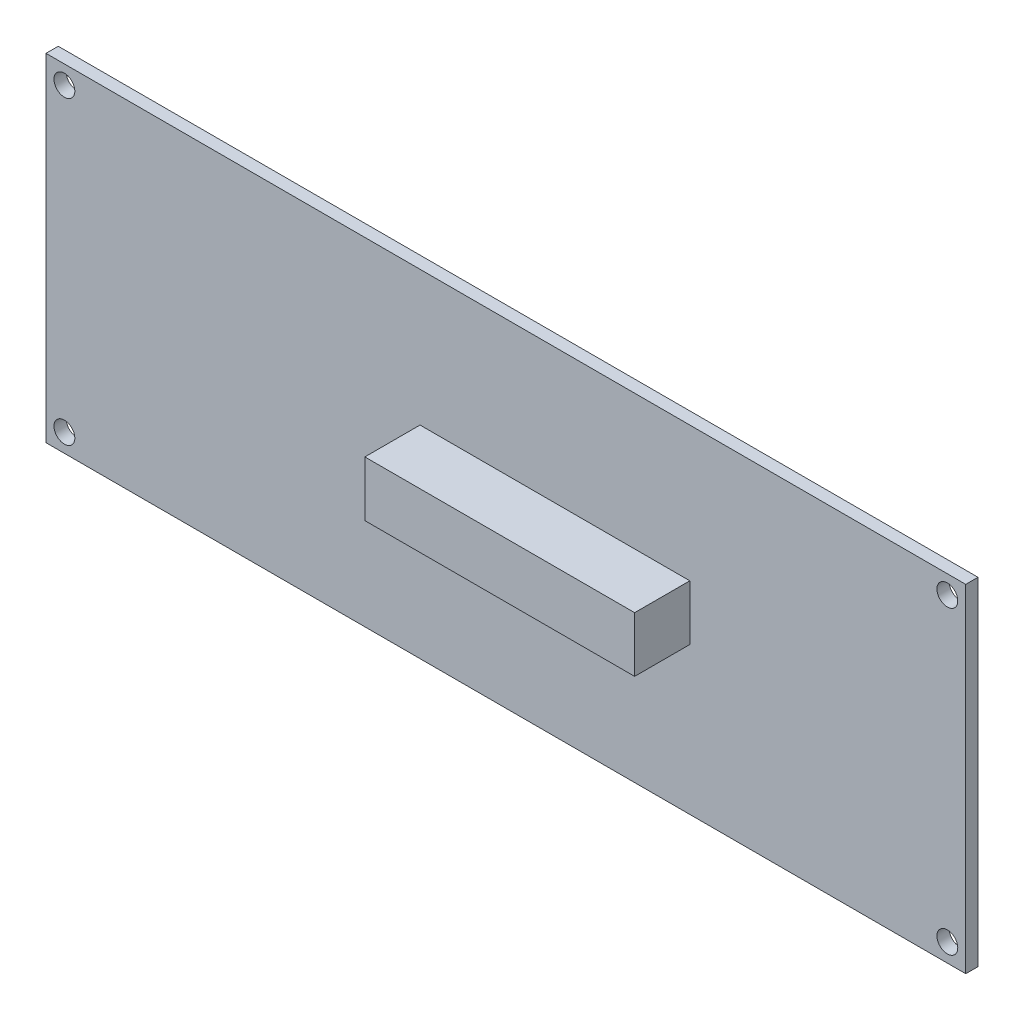
SolidWorks part; units mm, degrees
ref_plane "前基準面" through (0, 0, 0) normal (0, 0, 1) x (1, 0, 0)
ref_plane "上基準面" through (0, 0, 0) normal (0, 1, 0) x (1, 0, 0)
ref_plane "右基準面" through (0, 0, 0) normal (1, 0, 0) x (0, 0, -1)
sketch "草圖1" plane through (0, 0, 0) normal (0, 0, 1) x (1, 0, 0)
  line L0 (0, 27.5) -> (0, -27.5) construction
  line L1 (-75, 27.5) -> (75, 27.5)
  line L2 (-75, 27.5) -> (-75, -27.5)
  line L3 (-75, -27.5) -> (75, -27.5)
  line L4 (75, 27.5) -> (75, -27.5)
  line L6 (-75, 0) -> (75, 0) construction
  circle A0 centre (-72, 24.5) radius 1.7
  circle A1 centre (72, 24.5) radius 1.7
  circle A2 centre (72, -24.5) radius 1.7
  circle A3 centre (-72, -24.5) radius 1.7
  point P4 (0, 27.5)
  point P6 (-75, 0)
  dimension "D5" = 3.4
  dimension "D1" = 150
  dimension "D2" = 55
  dimension "D3" = 3
  dimension "D4" = 3
extrude "填料-伸長1" add sketch "草圖1" along normal blind 2
sketch "草圖2" plane through (0, 0, 2) normal (0, 0, 1) x (1, 0, 0)
  line L0 (75, 27.5) -> (-75, 27.5) construction
  line L1 (-14, 5.5) -> (30, 5.5)
  line L2 (-14, 5.5) -> (-14, -3.5)
  line L3 (-14, -3.5) -> (30, -3.5)
  line L4 (30, 5.5) -> (30, -3.5)
  line L5 (-75, 27.5) -> (-75, -27.5) construction
  dimension "D1" = 22
  dimension "D2" = 9
  dimension "D3" = 61
  dimension "D4" = 44
extrude "填料-伸長2" add sketch "草圖2" along normal blind 9
